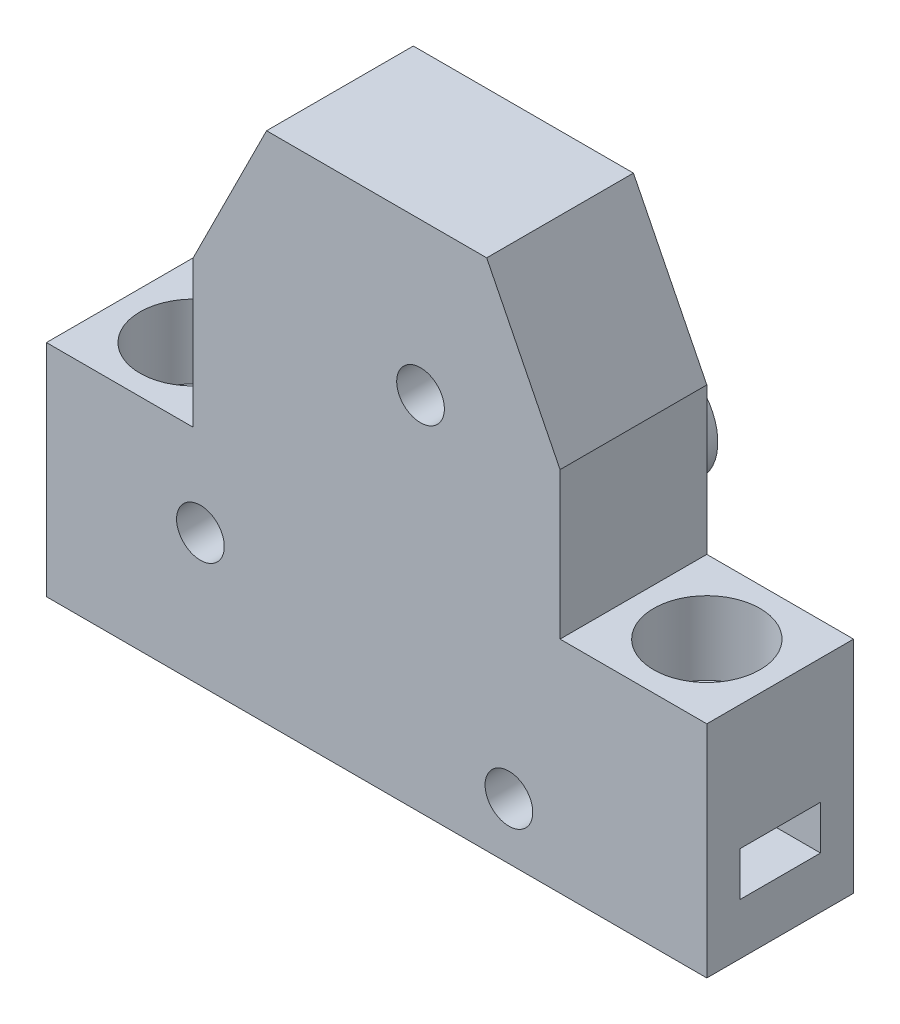
SolidWorks part; units mm, degrees
ref_plane "Front Plane" through (0, 0, 0) normal (0, 0, 1) x (1, 0, 0)
ref_plane "Top Plane" through (0, 0, 0) normal (0, 1, 0) x (1, 0, 0)
ref_plane "Right Plane" through (0, 0, 0) normal (1, 0, 0) x (0, 0, -1)
sketch "Sketch1" plane through (0, 0, 0) normal (0, 0, 1) x (1, 0, 0)
  line L0 (-25, 25) -> (-15, 45)
  line L1 (25, -25) -> (-25, -25)
  line L2 (25, -25) -> (25, 25) construction
  line L4 (-25, -25) -> (-25, 25) construction
  line L5 (25, -25) -> (-25, 25) construction
  line L6 (25, 25) -> (-25, -25) construction
  line L7 (-15, 45) -> (15, 45)
  line L8 (15, 45) -> (25, 25)
  line L9 (0, -1000) -> (0, 49000) construction
  line L10 (-25, -25) -> (-45, -25)
  line L12 (-25, 5) -> (-45, 5)
  line L13 (-45, -25) -> (-45, 5)
  line L14 (25, 5) -> (45, 5)
  line L15 (45, -25) -> (45, 5)
  line L16 (25, -25) -> (45, -25)
  line L17 (-25, 5) -> (-25, 25)
  line L18 (25, 5) -> (25, 25)
  point P0 (0, 0)
  point P6 (0, 45)
  dimension "D3" = 30
  dimension "D1" = 30
  dimension "D2" = 50
  dimension "D4" = 70
  dimension "D5" = 20
extrude "Body" add sketch "Sketch1" along normal mid plane 20
sketch "Sketch14" plane through (0, 0, -10) normal (0, 0, -1) x (-1, 0, 0)
  circle A0 centre (0, 0) radius 7.5
  dimension "D1" = 15
extrude "Bearing_Support" add sketch "Sketch14" along normal blind 15
sketch "Sketch15" plane through (0, 0, -25) normal (0, 0, -1) x (-1, 0, 0)
  circle A0 centre (0, 0) radius 4.7
  circle A1 centre (0, 0) radius 7.5
  circle A2 centre (0, 0) radius 7.5
  dimension "D2" = 9.4
  dimension "D1" = 0
extrude "Bearing_Place" add sketch "Sketch15" along normal blind 4
sketch "Sketch16" plane through (0, 0, -25) normal (0, 0, -1) x (-1, 0, 0)
  circle A0 centre (0, 0) radius 2
  dimension "D1" = 4
extrude "Motor_Shaft_Hole" cut sketch "Sketch16" against normal blind 3
fillet "Fillet1" radius 6 1 edges at (-7.5, 0, -10)
sketch "Sketch17" plane through (0, 5, 0) normal (0, 1, 0) x (1, 0, 0)
  line L0 (-45, 10) -> (-25, -10) construction
  circle A0 centre (-35, 0) radius 7.25
  dimension "D1" = 14.5
extrude "Spring_Hole" cut sketch "Sketch17" against normal blind 10
sketch "Sketch18" plane through (-45, 0, 0) normal (-1, 0, 0) x (0, 0, 1)
  line L0 (10, -25) -> (-10, -25) construction
  line L1 (5.5, -18) -> (-5.5, -18)
  line L2 (5.5, -18) -> (5.5, -12)
  line L3 (5.5, -12) -> (-5.5, -12)
  line L4 (-5.5, -18) -> (-5.5, -12)
  line L5 (5.5, -18) -> (-5.5, -12) construction
  line L6 (5.5, -12) -> (-5.5, -18) construction
  point P0 (0, -15)
  dimension "D1" = 11
  dimension "D2" = 6
  dimension "D3" = 10
extrude "Nut_Hole" cut sketch "Sketch18" against normal blind 20
sketch "Sketch19" plane through (0, -5, 0) normal (0, 1, 0) x (1, 0, 0)
  circle A0 centre (-35, 0) radius 3.25
  dimension "D1" = 6.5
extrude "Shaft_Hole" cut sketch "Sketch19" against normal up to surface (13 mm away) up to face at (-35, -18, 0)
mirror "Mirror1" about plane through (0, 0, 0) normal (1, 0, 0) of "Spring_Hole", "Nut_Hole", "Shaft_Hole"
sketch "Sketch20" plane through (0, 0, -10) normal (0, 0, -1) x (-1, 0, 0)
  circle A0 centre (-5.9824, 24.2737) radius 3.25
  circle A1 centre (24.0128, -6.9559) radius 3.25
  circle A2 centre (-18.0304, -17.3177) radius 3.25
  dimension "D1" = 6.5
extrude "Brake_Disk_Holes" cut sketch "Sketch20" against normal through all
